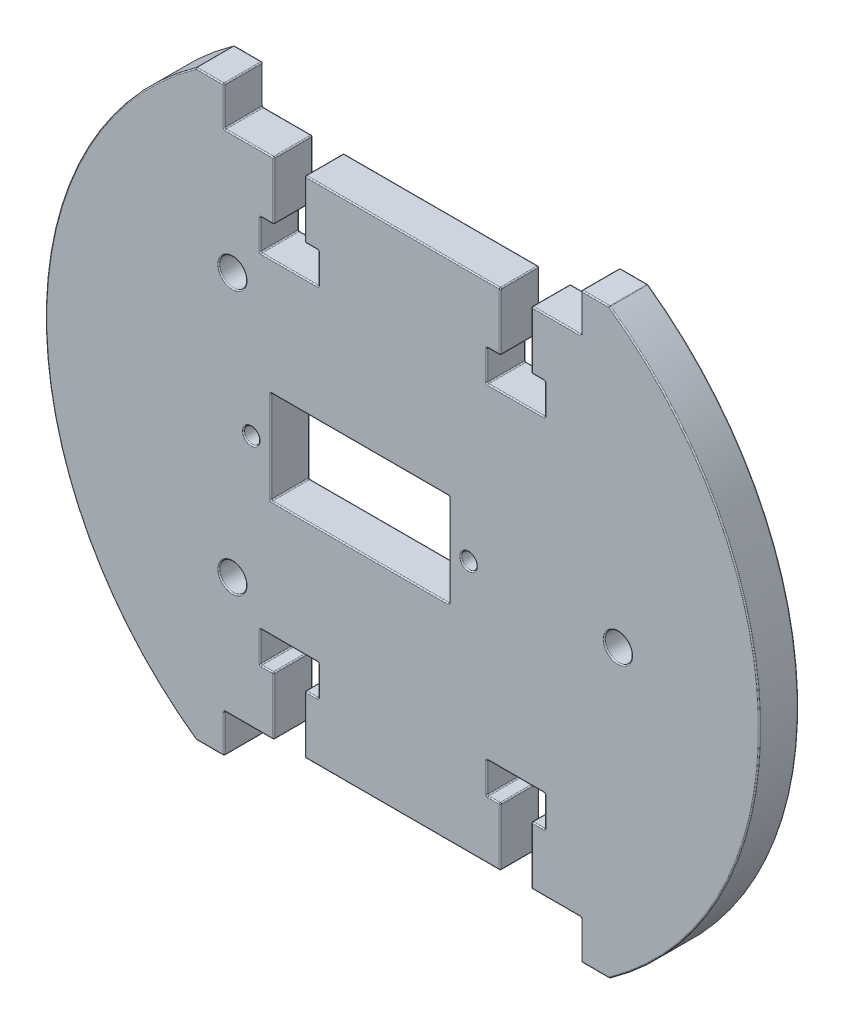
SolidWorks part; units mm, degrees
material "AISI 1020"
ref_plane "Front Plane" through (0, 0, 0) normal (0, 0, 1) x (1, 0, 0)
ref_plane "Top Plane" through (0, 0, 0) normal (0, 1, 0) x (1, 0, 0)
ref_plane "Right Plane" through (0, 0, 0) normal (1, 0, 0) x (0, 0, -1)
sketch "Sketch1" plane through (0, 0, 0) normal (0, 0, 1) x (1, 0, 0)
  line L0 (-26.6411, 37.5) -> (-23, 37.5)
  line L2 (-23, 37.5) -> (-23, 32.5)
  line L3 (23, 37.5) -> (23, 32.5)
  line L4 (-23, 32.5) -> (23, 32.5)
  line L5 (23, 37.5) -> (26.6411, 37.5)
  line L6 (0, 0) -> (-46, 0) construction
  line L7 (23, -37.5) -> (26.6411, -37.5)
  line L8 (-26.6411, -37.5) -> (-23, -37.5)
  line L9 (-23, -37.5) -> (-23, -32.5)
  line L10 (23, -37.5) -> (23, -32.5)
  line L11 (-23, -32.5) -> (23, -32.5)
  line L12 (-5.5, 0) -> (-5.5, 6) construction
  line L13 (6, 6) -> (-17, 6)
  line L14 (6, 6) -> (6, -6)
  line L15 (6, -6) -> (-17, -6)
  line L16 (-17, 6) -> (-17, -6)
  line L17 (6, 6) -> (-17, -6) construction
  line L18 (6, -6) -> (-17, 6) construction
  line L19 (-21.93, 0) -> (27.75, 0) construction
  line L20 (-21.93, 17) -> (-21.93, -17) construction
  arc A0 (-26.6411, 37.5) -> (-26.6411, -37.5) centre (0, 0) ccw
  arc A1 (26.6411, -37.5) -> (26.6411, 37.5) centre (0, 0) ccw
  circle A2 centre (8.5, 0) radius 1
  circle A3 centre (-19.5, 0) radius 1
  circle A4 centre (-21.93, 17) radius 1.75
  circle A5 centre (-21.93, -17) radius 1.75
  circle A6 centre (27.75, 0) radius 1.75
  point P5 (0, 32.5)
  point P18 (-5.5, 0)
  point P25 (6, 0)
  dimension "D1" = 92
  dimension "D8" = 2
  dimension "D13" = 3.5
  dimension "D2" = 37.5
  dimension "D3" = 5
  dimension "D4" = 46
  dimension "D5" = 23
  dimension "D6" = 12
  dimension "D7" = 6
  dimension "D9" = 2.5
  dimension "D10" = 34
  dimension "D11" = 27.75
  dimension "D12" = 49.68
extrude "Boss-Extrude1" add sketch "Sketch1" along normal blind 5
sketch "Sketch2" plane through (0, 0, 5) normal (0, 0, 1) x (1, 0, 0)
  line L0 (23, 32.5) -> (-23, 32.5) construction
  line L1 (-12.6, 25) -> (-16.6, 25)
  line L2 (-12.6, 25) -> (-12.6, 32.5)
  line L3 (-12.6, 32.5) -> (-16.6, 32.5)
  line L4 (-16.6, 25) -> (-16.6, 32.5)
  line L5 (-12.6, 25) -> (-16.6, 32.5) construction
  line L6 (-12.6, 32.5) -> (-16.6, 25) construction
  line L7 (-23, 32.5) -> (-23, 37.5) construction
  line L8 (-10.85, 21) -> (-18.35, 21)
  line L9 (-10.85, 21) -> (-10.85, 25)
  line L10 (-10.85, 25) -> (-18.35, 25)
  line L11 (-18.35, 21) -> (-18.35, 25)
  line L12 (-10.85, 21) -> (-18.35, 25) construction
  line L13 (-10.85, 25) -> (-18.35, 21) construction
  line L14 (0, 0) -> (-17, 0) construction
  line L16 (-17, 6) -> (-17, -6) construction
  line L17 (0, 0) -> (0, 32.5) construction
  line L18 (10.85, 25) -> (18.35, 21) construction
  line L19 (10.85, 21) -> (18.35, 25) construction
  line L20 (12.6, 32.5) -> (16.6, 25) construction
  line L21 (12.6, 25) -> (16.6, 32.5) construction
  line L22 (18.35, 21) -> (18.35, 25)
  line L23 (10.85, 25) -> (18.35, 25)
  line L24 (10.85, 21) -> (10.85, 25)
  line L25 (10.85, 21) -> (18.35, 21)
  line L26 (16.6, 25) -> (16.6, 32.5)
  line L27 (12.6, 32.5) -> (16.6, 32.5)
  line L28 (12.6, 25) -> (12.6, 32.5)
  line L29 (12.6, 25) -> (16.6, 25)
  line L30 (12.6, -25) -> (16.6, -32.5) construction
  line L31 (12.6, -32.5) -> (16.6, -25) construction
  line L32 (10.85, -21) -> (18.35, -25) construction
  line L33 (10.85, -25) -> (18.35, -21) construction
  line L34 (-10.85, -25) -> (-18.35, -21) construction
  line L35 (-10.85, -21) -> (-18.35, -25) construction
  line L36 (-12.6, -32.5) -> (-16.6, -25) construction
  line L37 (-12.6, -25) -> (-16.6, -32.5) construction
  line L38 (12.6, -25) -> (16.6, -25)
  line L39 (12.6, -25) -> (12.6, -32.5)
  line L40 (12.6, -32.5) -> (16.6, -32.5)
  line L41 (16.6, -25) -> (16.6, -32.5)
  line L42 (10.85, -21) -> (18.35, -21)
  line L43 (10.85, -21) -> (10.85, -25)
  line L44 (10.85, -25) -> (18.35, -25)
  line L45 (18.35, -21) -> (18.35, -25)
  line L46 (-18.35, -21) -> (-18.35, -25)
  line L47 (-10.85, -25) -> (-18.35, -25)
  line L48 (-10.85, -21) -> (-10.85, -25)
  line L49 (-10.85, -21) -> (-18.35, -21)
  line L50 (-16.6, -25) -> (-16.6, -32.5)
  line L51 (-12.6, -32.5) -> (-16.6, -32.5)
  line L52 (-12.6, -25) -> (-12.6, -32.5)
  line L53 (-12.6, -25) -> (-16.6, -25)
  point P0 (-14.6, 28.75)
  point P7 (-14.6, 23)
  point P29 (14.6, 23)
  point P30 (14.6, 28.75)
  point P47 (14.6, -28.75)
  point P48 (14.6, -23)
  point P49 (-14.6, -23)
  point P50 (-14.6, -28.75)
  line M21 (23, 32.5) -> (-23, 32.5)
  line M27 (-23, -32.5) -> (23, -32.5)
  dimension "D1" = 6.4
  dimension "D2" = 4
  dimension "D3" = 7.5
  dimension "D4" = 7.5
  dimension "D5" = 4
extrude "Cut-Extrude1" cut sketch "Sketch2" against normal blind 5 contours L11 L8 L9 L10 L1 | L4 L1 L2 M21 | L28 L23 L26 M21 | L24 L25 L22 L23 | L45 L42 L43 L44 L38 | L41 L38 L39 M27 | L52 L47 L50 M27
fillet "Fillet1" radius 0.15 123 edges at (-12.6, -25, 2.5) (-16.6, -28.75, 0) (-12.6, -28.75, 0) (-16.6, -28.75, 5) (-12.6, -28.75, 5) (-18.35, -21, 2.5) (-10.85, -21, 2.5) (-14.6, -21, 0) (-18.35, -23, 0) (-11.725, -25, 0) (-17.475, -25, 0) (-10.85, -23, 0) (-14.6, -21, 5) (-11.725, -25, 5) (-17.475, -25, 5) (18.35, -25, 2.5) (16.6, -25, 2.5) (16.6, -32.5, 2.5) (12.6, -32.5, 2.5) (12.6, -25, 2.5) (10.85, -25, 2.5) (10.85, -21, 2.5) (18.35, -21, 2.5) (17.475, -25, 0) (16.6, -28.75, 0) (12.6, -28.75, 0) (11.725, -25, 0) (10.85, -23, 0) (14.6, -21, 0) (18.35, -23, 0) (17.475, -25, 5) (16.6, -28.75, 5) (12.6, -28.75, 5) (11.725, -25, 5) (10.85, -23, 5) (14.6, -21, 5) (18.35, -23, 5) (12.6, 32.5, 2.5) (16.6, 25, 2.5) (18.35, 25, 2.5) (18.35, 21, 2.5) (10.85, 21, 2.5) (10.85, 25, 2.5) (12.6, 25, 2.5) (16.6, 28.75, 0) (17.475, 25, 0) (10.85, 23, 0) (12.6, 28.75, 0) (16.6, 28.75, 5) (17.475, 25, 5) (14.6, 21, 5) (10.85, 23, 5) (11.725, 25, 5) (12.6, 28.75, 5) (-18.35, 23, 5) (-14.6, 21, 5) (-10.85, 23, 5) (-11.725, 25, 5) (-12.6, 28.75, 5) (-16.6, 28.75, 5) (-17.475, 25, 5) (-14.6, 21, 0) (-10.85, 23, 0) (-12.6, 28.75, 0) (-16.6, 28.75, 0) (-18.35, 21, 2.5) (-10.85, 21, 2.5) (-10.85, 25, 2.5) (-12.6, 32.5, 2.5) (-16.6, 32.5, 2.5) (-18.35, 25, 2.5) (-20.18, 17, 5) (29.5, 0, 0) (-20.18, -17, 0) (-20.18, -17, 5) (-20.5, 0, 0) (-20.5, 0, 5) (9.5, 0, 5) (-17, 0, 0) (-5.5, -6, 0) (6, 0, 0) (-5.5, 6, 0) (-17, 0, 5) (-5.5, -6, 5) (6, 0, 5) (-17, 6, 2.5) (6, -6, 2.5) (-17, -6, 2.5) (23, -35, 0) (24.8206, -37.5, 0) (24.8206, 37.5, 0) (0, 32.5, 0) (19.8, 32.5, 0) (-23, 35, 0) (-24.8206, 37.5, 0) (-24.8206, -37.5, 0) (-23, -35, 0) (19.8, -32.5, 0) (0, -32.5, 0) (-19.8, -32.5, 0) (24.8206, -37.5, 5) (46, 0, 5) (24.8206, 37.5, 5) (-19.8, 32.5, 5) (0, 32.5, 5) (19.8, 32.5, 5) (-23, 35, 5) (-24.8206, 37.5, 5) (-46, 0, 5) (-23, -35, 5) (19.8, -32.5, 5) (0, -32.5, 5) (23, -32.5, 2.5) (-23, -32.5, 2.5) (-23, -37.5, 2.5) (-26.6411, -37.5, 2.5) (-26.6411, 37.5, 2.5) (-23, 37.5, 2.5) (-23, 32.5, 2.5) (23, 32.5, 2.5) (23, 37.5, 2.5) (26.6411, 37.5, 2.5) (-16.6, -32.5, 2.5)
